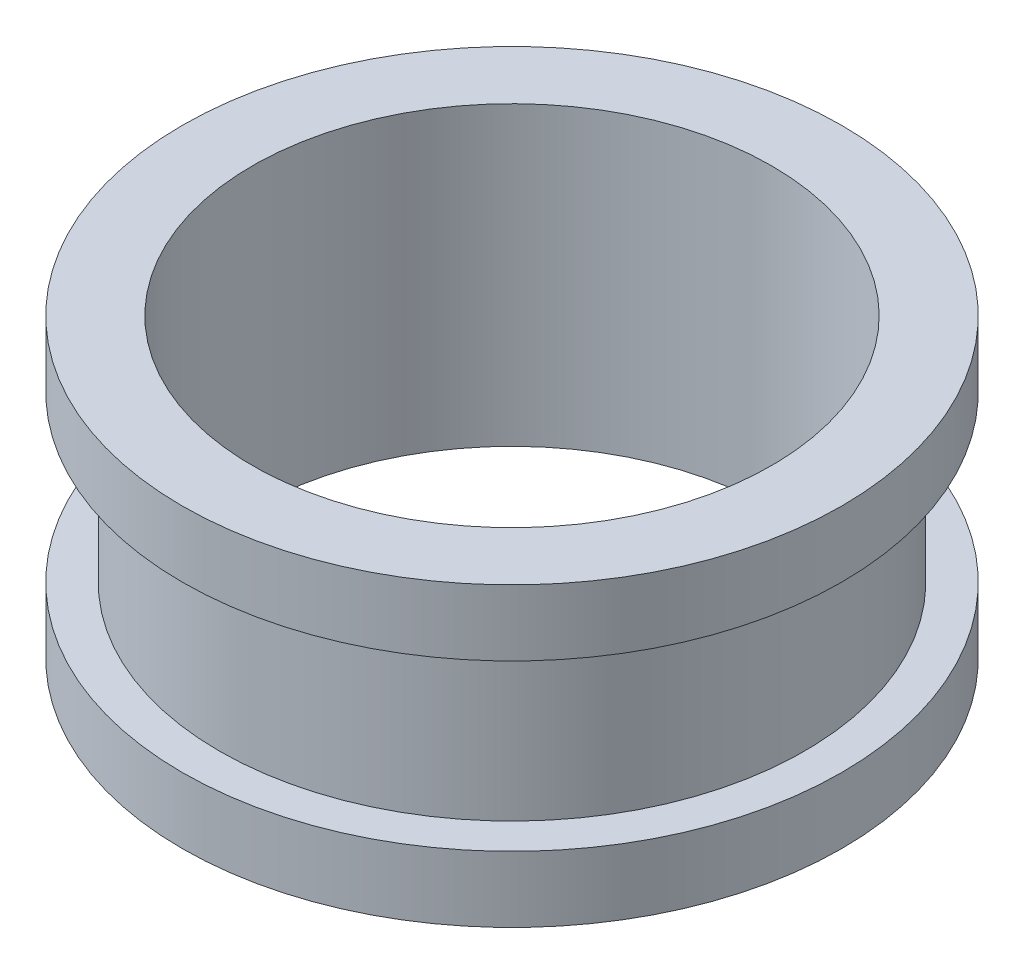
SolidWorks part; units mm, degrees
ref_plane "Front Plane" through (0, 0, 0) normal (0, 0, 1) x (1, 0, 0)
ref_plane "Top Plane" through (0, 0, 0) normal (0, 1, 0) x (1, 0, 0)
ref_plane "Right Plane" through (0, 0, 0) normal (1, 0, 0) x (0, 0, -1)
sketch "Sketch1" plane through (0, 0, 0) normal (0, 0, 1) x (1, 0, 0)
  line L0 (0, -200) -> (0, 100) construction
  line L1 (3.15, -0.8) -> (3.15, 2.8)
  line L2 (3.15, 2.8) -> (4, 2.8)
  line L3 (4, 2.8) -> (4, 2)
  line L4 (4, 2) -> (3.55, 2)
  line L5 (3.55, 2) -> (3.55, 0)
  line L6 (3.55, 0) -> (4, 0)
  line L7 (4, 0) -> (4, -0.8)
  line L8 (4, -0.8) -> (3.15, -0.8)
revolve "Revolve1" add sketch "Sketch1" angle 360 about L0
